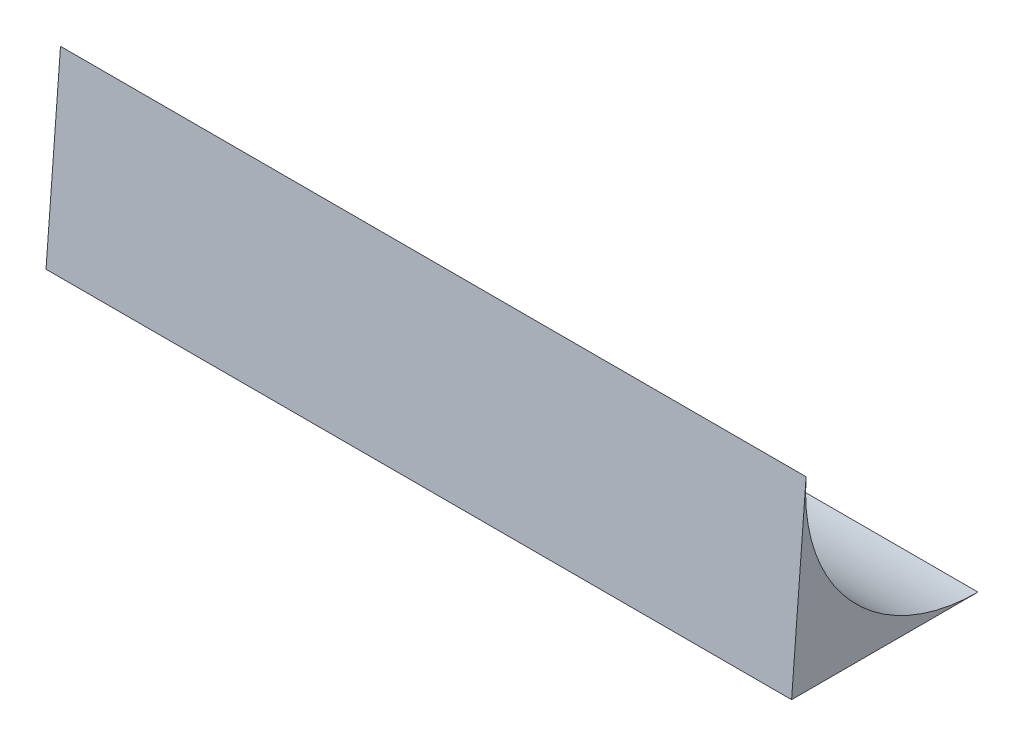
SolidWorks part; units mm, degrees
ref_plane "前视基准面" through (0, 0, 0) normal (0, 0, 1) x (1, 0, 0)
ref_plane "上视基准面" through (0, 0, 0) normal (0, 1, 0) x (1, 0, 0)
ref_plane "右视基准面" through (0, 0, 0) normal (1, 0, 0) x (0, 0, -1)
sketch "Sketch1" plane through (0, 0, 0) normal (1, 0, 0) x (0, 0, -1)
  line L0 (0, 0) -> (10, 0)
  line L1 (10, 0) -> (10, 9.25) construction
  line L2 (0, 0) -> (0.778, 9.9697)
  line L3 (10, 0) -> (20, 0) construction
  arc A0 (0.778, 9.9697) -> (10, 0) centre (10, 9.25) ccw
  arc A1 (10, 0) -> (0.778, 9.9697) centre (10, 9.25) ccw construction
  point P5 (0, 0)
  point P6 (0, 0)
  dimension "D2" = 18.5
  dimension "D1" = 20
  dimension "D3" = 10
extrude "Boss-Extrude1" add sketch "Sketch1" along normal blind 40
